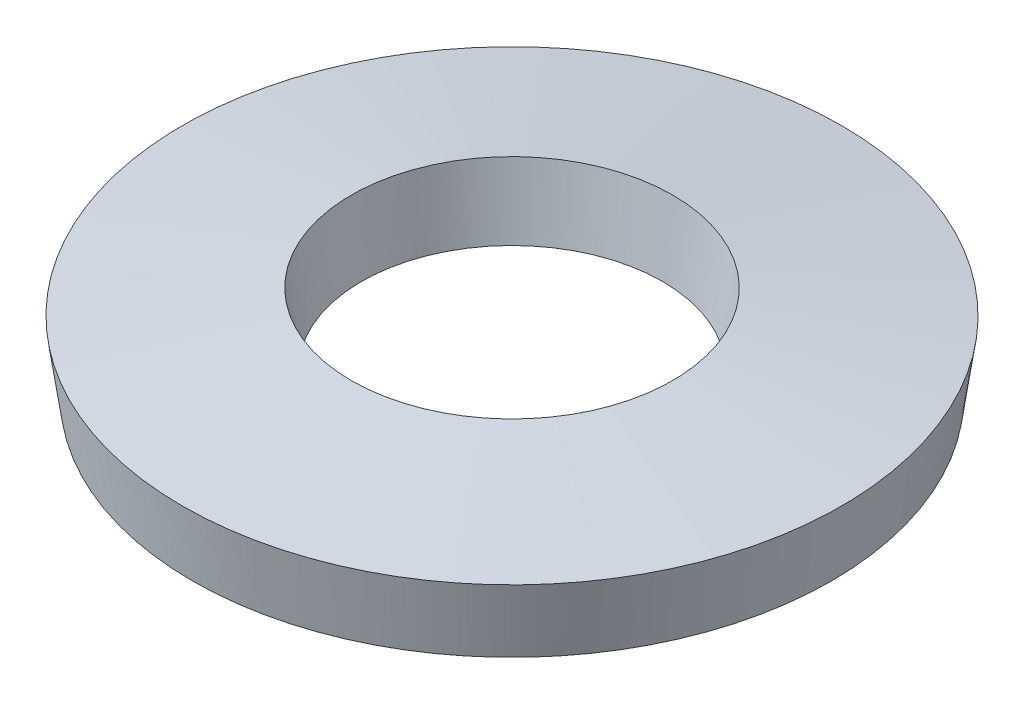
SolidWorks part; units mm, degrees
ref_plane "Front" through (0, 0, 0) normal (0, 0, 1) x (1, 0, 0)
ref_plane "Top" through (0, 0, 0) normal (0, 1, 0) x (1, 0, 0)
ref_plane "Right" through (0, 0, 0) normal (1, 0, 0) x (0, 0, -1)
sketch "Sketch1" plane through (0, 0, 0) normal (0, 0, 1) x (1, 0, 0)
  line L0 (6.7867, 0) -> (3.2, 0.5152)
  line L1 (3.2, 0.5152) -> (3.4133, 2)
  line L2 (3.4133, 2) -> (7, 1.4848)
  line L3 (7, 1.4848) -> (6.7867, 0)
  line L4 (0, 0) -> (0, 2) construction
  point P5 (3.3066, 1.2576)
  dimension "D1" = 3.6235
  dimension "ID" = 6.4
  dimension "OD" = 14
  dimension "Thickness" = 1.5
  dimension "Height" = 2
revolve "Revolve1" add sketch "Sketch1" angle 360 about L4
sketch "Sketch15" plane through (0, 0, 0) normal (0, 1, 0) x (1, 0, 0)
  circle A0 centre (0, 0) radius 7
  circle A1 centre (0, 0) radius 3.2
